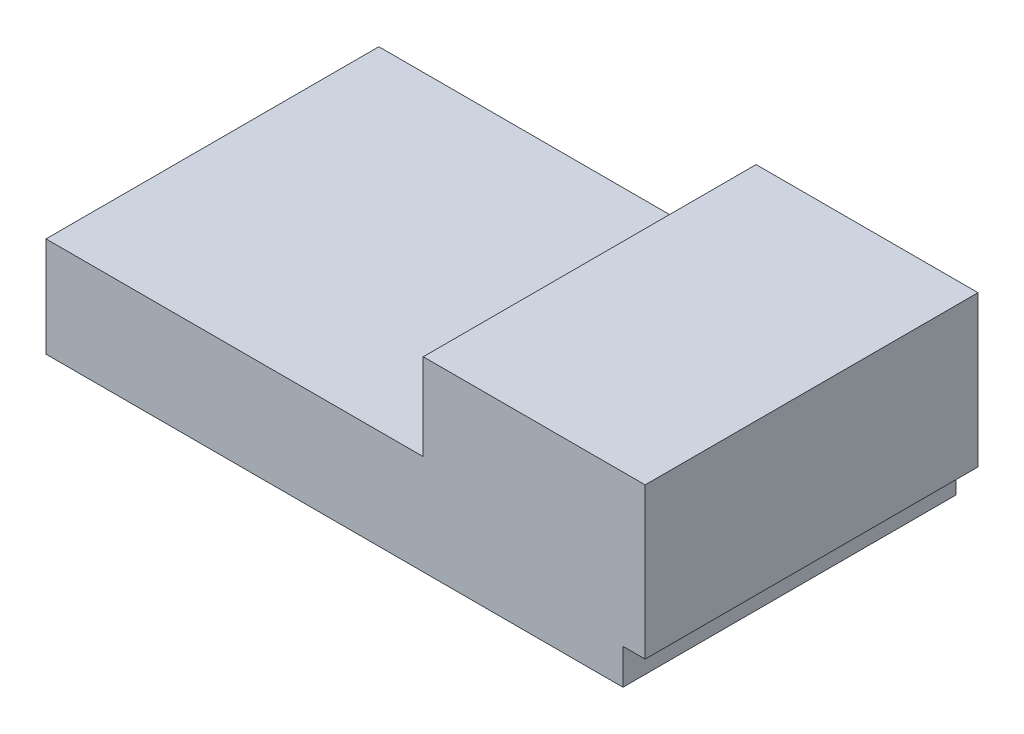
SolidWorks part; units mm, degrees
ref_plane "Front Plane" through (0, 0, 0) normal (0, 0, 1) x (1, 0, 0)
ref_plane "Top Plane" through (0, 0, 0) normal (0, 1, 0) x (1, 0, 0)
ref_plane "Right Plane" through (0, 0, 0) normal (1, 0, 0) x (0, 0, -1)
sketch "Sketch1" plane through (0, 0, 0) normal (0, 0, 1) x (1, 0, 0)
  line L0 (0, 0) -> (0, 4.5)
  line L1 (0, 4.5) -> (17, 4.5)
  line L2 (17, 4.5) -> (17, 8.4)
  line L3 (17, 8.4) -> (27, 8.4)
  line L4 (27, 8.4) -> (27, 1.6)
  line L5 (27, 1.6) -> (26, 1.6)
  line L6 (26, 1.6) -> (26, 0)
  line L7 (26, 0) -> (0, 0)
  dimension "D1" = 26
  dimension "D2" = 27
  dimension "D3" = 4.5
  dimension "D4" = 1.6
  dimension "D5" = 8.4
  dimension "D6" = 10
extrude "Boss-Extrude1" add sketch "Sketch1" along normal blind 15
